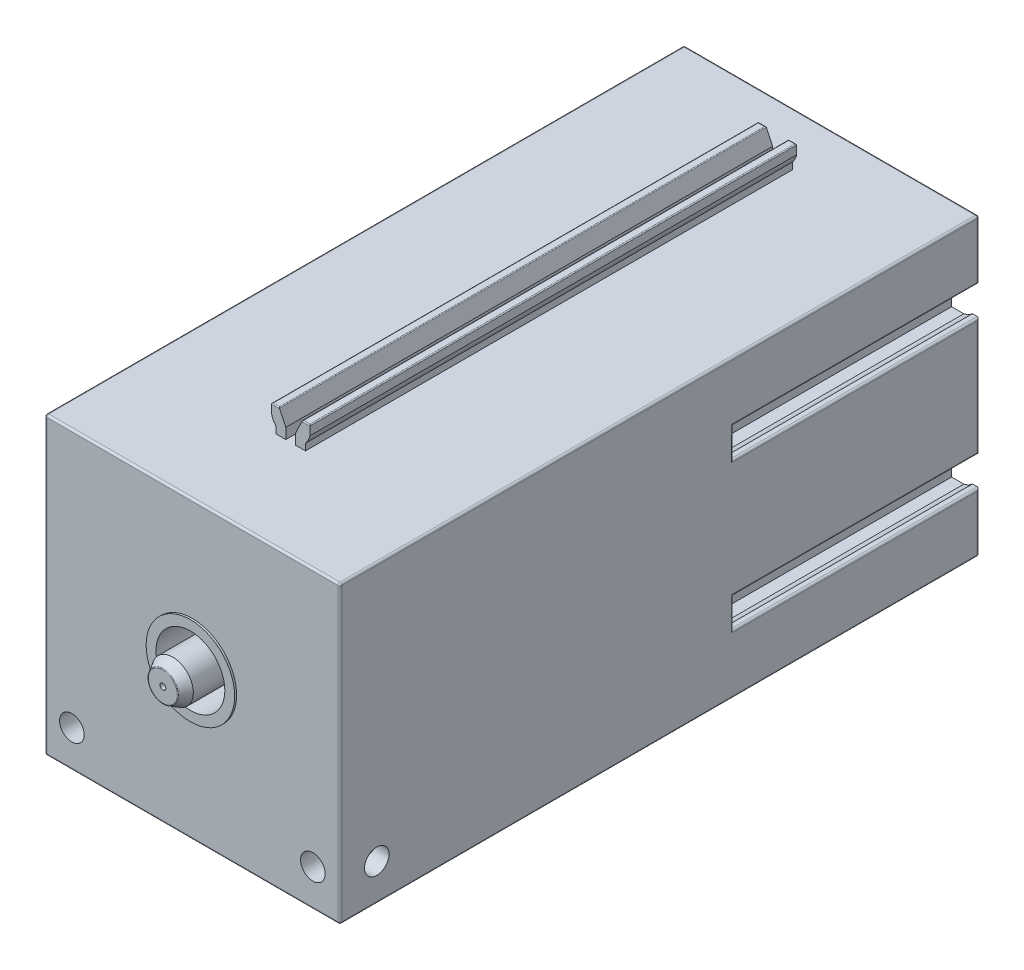
SolidWorks part; units mm, degrees
ref_plane "前视基准面" through (0, 0, 0) normal (0, 0, 1) x (1, 0, 0)
ref_plane "上视基准面" through (0, 0, 0) normal (0, 1, 0) x (1, 0, 0)
ref_plane "右视基准面" through (0, 0, 0) normal (1, 0, 0) x (0, 0, -1)
sketch "草图1" plane through (0, 0, 0) normal (0, 0, 1) x (1, 0, 0)
  line L1 (-15, 0) -> (15, 0)
  line L2 (-15, 0) -> (-15, 30)
  line L3 (-15, 30) -> (15, 30)
  line L4 (15, 0) -> (15, 30)
extrude "凸台-拉伸1" add sketch "草图1" against normal blind 65
sketch "草图2" plane through (0, 0, -65) normal (0, 0, -1) x (-1, 0, 0)
  line L0 (-9, 0.6771) -> (-9, 0)
  line L1 (15, 0) -> (-15, 0) construction
  line L2 (0, -2.0675) -> (0, 3.9748) construction
  line L3 (-6, 0.6771) -> (-6, 0)
  line L4 (-6, 0) -> (-9, 0)
  line L5 (-9.45, 2.8) -> (-5.55, 2.8)
  line L6 (-9.45, 2.8) -> (-9.45, 1.5556)
  line L7 (5.55, 2.8) -> (5.55, 1.5556)
  line L8 (-5.55, 2.8) -> (-5.55, 1.5556)
  line L9 (9.45, 2.8) -> (9.45, 1.5556)
  line L10 (9.45, 2.8) -> (5.55, 2.8)
  line L11 (6, 0) -> (9, 0)
  line L12 (6, 0.6771) -> (6, 0)
  line L13 (9, 0.6771) -> (9, 0)
  arc A0 (9.45, 1.5556) -> (9, 0.6771) centre (7.5, 2) cw
  arc A1 (-6, 0.6771) -> (-5.55, 1.5556) centre (-7.5, 2) ccw
  arc A2 (-9.45, 1.5556) -> (-9, 0.6771) centre (-7.5, 2) ccw
  arc A3 (6, 0.6771) -> (5.55, 1.5556) centre (7.5, 2) cw
extrude "切除-拉伸1" cut sketch "草图2" against normal blind 54
sketch "草图3" plane through (0, 0, -65) normal (0, 0, -1) x (-1, 0, 0)
  line L0 (-14.3229, 9) -> (-15, 9)
  line L1 (-15, 0) -> (-15, 30) construction
  line L2 (-15, 6) -> (-14.3229, 6)
  line L3 (-12.2, 9.45) -> (-12.2, 5.55)
  line L4 (-15, 9) -> (-15, 6)
  line L5 (-12.2, 5.55) -> (-13.4444, 5.55)
  line L6 (-12.2, 9.45) -> (-13.4444, 9.45)
  line L8 (-12.2, 20.55) -> (-13.4444, 20.55)
  line L9 (-12.2, 24.45) -> (-13.4444, 24.45)
  line L10 (-15, 21) -> (-15, 24)
  line L11 (-12.2, 20.55) -> (-12.2, 24.45)
  line L12 (-15, 24) -> (-14.3229, 24)
  line L13 (-14.3229, 21) -> (-15, 21)
  line L15 (14.3229, 21) -> (15, 21)
  line L16 (15, 24) -> (14.3229, 24)
  line L17 (12.2, 20.55) -> (12.2, 24.45)
  line L18 (15, 21) -> (15, 24)
  line L19 (12.2, 24.45) -> (13.4444, 24.45)
  line L20 (12.2, 20.55) -> (13.4444, 20.55)
  line L21 (12.2, 9.45) -> (13.4444, 9.45)
  line L22 (12.2, 5.55) -> (13.4444, 5.55)
  line L23 (15, 9) -> (15, 6)
  line L24 (12.2, 9.45) -> (12.2, 5.55)
  line L25 (15, 6) -> (14.3229, 6)
  line L26 (14.3229, 9) -> (15, 9)
  arc A0 (-14.3229, 6) -> (-13.4444, 5.55) centre (-13, 7.5) ccw
  arc A1 (-13.4444, 9.45) -> (-14.3229, 9) centre (-13, 7.5) ccw
  arc A2 (-13.4444, 20.55) -> (-14.3229, 21) centre (-13, 22.5) cw
  arc A3 (-14.3229, 24) -> (-13.4444, 24.45) centre (-13, 22.5) cw
  arc A4 (14.3229, 24) -> (13.4444, 24.45) centre (13, 22.5) ccw
  arc A5 (13.4444, 20.55) -> (14.3229, 21) centre (13, 22.5) ccw
  arc A6 (13.4444, 9.45) -> (14.3229, 9) centre (13, 7.5) cw
  arc A7 (14.3229, 6) -> (13.4444, 5.55) centre (13, 7.5) cw
extrude "切除-拉伸2" cut sketch "草图3" against normal blind 25
sketch "草图5" plane through (0, 0, -65) normal (0, 0, -1) x (-1, 0, 0)
  line L0 (-1.5, 30.6771) -> (-1.5, 30)
  line L1 (-15, 30) -> (15, 30) construction
  line L2 (1.5, 30) -> (1.5, 30.6771)
  line L3 (-1.95, 32.5) -> (-1.1658, 32.5)
  line L4 (-1.95, 32.5) -> (-1.95, 31.5556)
  line L5 (1.95, 32.5) -> (1.95, 31.5556)
  line L6 (-1.5, 30) -> (-0.5, 30)
  line L7 (-0.5, 30) -> (-0.5, 31.0723)
  line L8 (0.5, 30) -> (0.5, 31.0723)
  line L9 (-0.5, 31.0723) -> (-1.1658, 32.5)
  line L10 (0.5, 31.0723) -> (1.1658, 32.5)
  line L11 (1.1658, 32.5) -> (1.95, 32.5)
  line L12 (0.5, 30) -> (1.5, 30)
  arc A1 (-1.95, 31.5556) -> (-1.5, 30.6771) centre (0, 32) ccw
  arc A2 (1.5, 30.6771) -> (1.95, 31.5556) centre (0, 32) ccw
extrude "凸台-拉伸2" add sketch "草图5" against normal blind 49.5 from offset 5.5 offset against normal yes
fillet "圆角1" radius 0.1 8 edges at (-1.1658, 32.5, -34.75) (-1.5579, 32.5, -10) (-1.95, 32.5, -34.75) (-1.5579, 32.5, -59.5) (1.95, 32.5, -34.75) (1.5579, 32.5, -10) (1.1658, 32.5, -34.75) (1.5579, 32.5, -59.5)
sketch "草图6" plane through (0, 0, 0) normal (0, 0, 1) x (1, 0, 0)
  circle A0 centre (0, 15) radius 3.5
extrude "切除-拉伸3" cut sketch "草图6" against normal blind 5
sketch "草图7" plane through (0, 0, 0) normal (0, 0, 1) x (1, 0, 0)
  circle A0 centre (0, 15) radius 4.5
  circle A1 centre (0, 15) radius 3.5
extrude "凸台-拉伸3" add sketch "草图7" along normal blind 0.2
sketch "草图8" plane through (0, 0, -5) normal (0, 0, 1) x (1, 0, 0)
  circle A0 centre (0, 15) radius 2.1
extrude "凸台-拉伸4" add sketch "草图8" along normal blind 8
sketch "草图9" plane through (0, 0, 3) normal (0, 0, 1) x (1, 0, 0)
  circle A0 centre (0, 15) radius 0.3
extrude "切除-拉伸4" cut sketch "草图9" against normal blind 8
chamfer "倒角1" distance 1 angle 30 1 edges at (2.1, 15, 3)
fillet "圆角2" radius 0.1 1 edges at (1.5226, 15, 3)
fillet "圆角3" radius 0.2 36 edges at (-12, 0, -65) (0, 0, 0) (12, 0, -65) (9, 0, -38) (7.5, 0, -11) (6, 0, -38) (0, 0, -65) (-6, 0, -38) (-7.5, 0, -11) (-9, 0, -38) (-15, 15, -65) (-15, 21, -52.5) (-15, 22.5, -40) (-15, 24, -52.5) (-15, 27, -65) (-15, 30, -32.5) (-15, 15, 0) (-15, 0, -32.5) (-15, 3, -65) (-15, 6, -52.5) (-15, 7.5, -40) (-15, 9, -52.5) (15, 15, -65) (15, 9, -52.5) (15, 7.5, -40) (15, 6, -52.5) (15, 3, -65) (15, 0, -32.5) (15, 15, 0) (15, 30, -32.5) (15, 27, -65) (15, 24, -52.5) (15, 22.5, -40) (15, 21, -52.5) (0, 30, -65) (0, 30, 0)
sketch "草图10" plane through (0, 0, 0) normal (0, 0, 1) x (1, 0, 0)
  circle A0 centre (-12.25, 3.75) radius 1.25
  circle A1 centre (12.25, 3.75) radius 1.25
extrude "切除-拉伸5" cut sketch "草图10" against normal blind 5
sketch "草图11" plane through (15, 0, 0) normal (1, 0, 0) x (0, 0, -1)
  circle A0 centre (3.75, 3.75) radius 1.25
extrude "切除-拉伸6" cut sketch "草图11" against normal blind 5
sketch "草图12" plane through (-15, 0, 0) normal (-1, 0, 0) x (0, 0, 1)
  circle A0 centre (-3.75, 3.75) radius 1.25
extrude "切除-拉伸7" cut sketch "草图12" against normal blind 5
